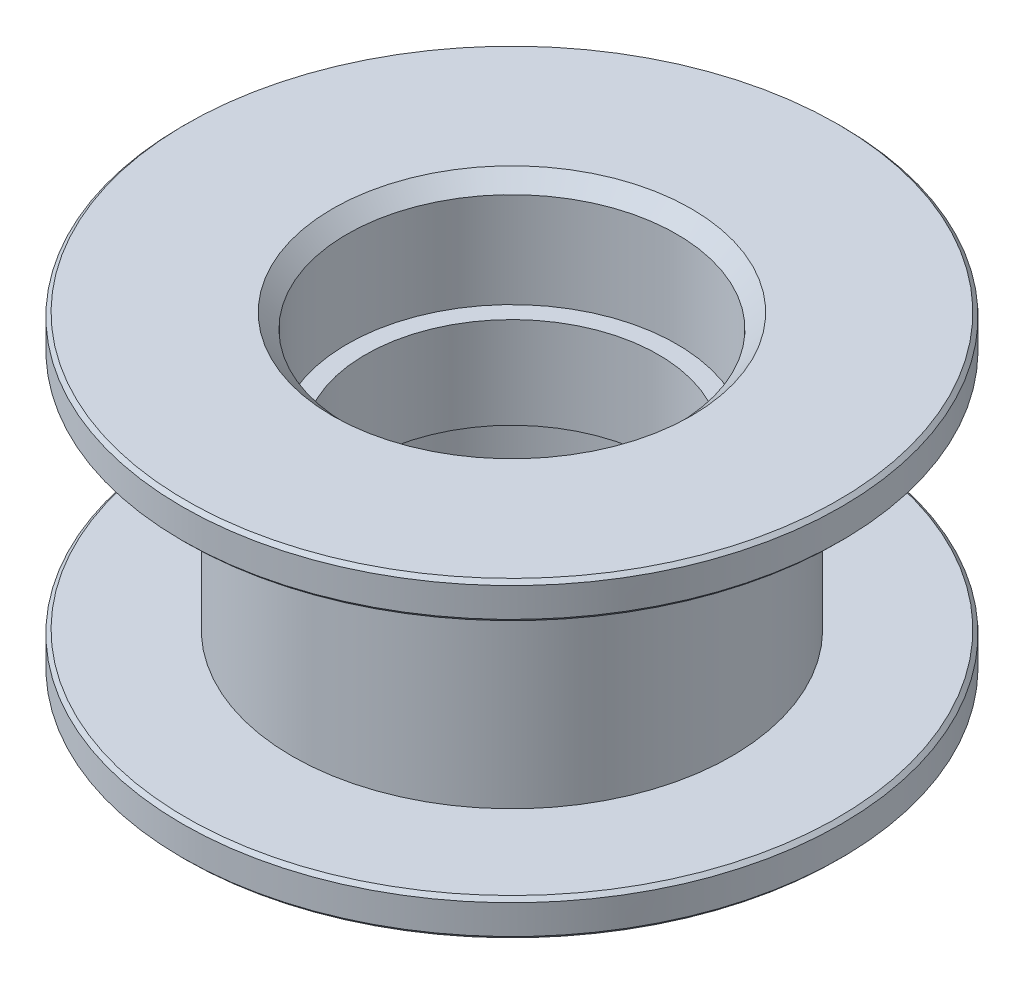
SolidWorks part; units mm, degrees
material "6061 Alloy"
ref_plane "Front Plane" through (0, 0, 0) normal (0, 0, 1) x (1, 0, 0)
ref_plane "Top Plane" through (0, 0, 0) normal (0, 1, 0) x (1, 0, 0)
ref_plane "Right Plane" through (0, 0, 0) normal (1, 0, 0) x (0, 0, -1)
sketch "BodyS" plane through (0, 0, 0) normal (0, 0, 1) x (1, 0, 0)
  line L0 (6, -3.25) -> (6, 3.25)
  line L1 (6, 3.25) -> (9, 3.25)
  line L2 (9, 3.25) -> (9, 4.25)
  line L3 (9, 4.25) -> (4.5, 4.25)
  line L4 (4.5, 4.25) -> (4.5, 1.25)
  line L5 (4.5, 1.25) -> (4, 1.25)
  line L6 (4, 1.25) -> (4, -1.25)
  line L7 (4, -1.25) -> (4.5, -1.25)
  line L8 (4.5, -1.25) -> (4.5, -4.25)
  line L9 (4.5, -4.25) -> (9, -4.25)
  line L10 (9, -4.25) -> (9, -3.25)
  line L11 (9, -3.25) -> (6, -3.25)
  line L12 (0, 0) -> (4, 0) construction
  line L13 (0, 4.25) -> (0, -4.25) construction
  dimension "BearingOD" = 9
  dimension "Height" = 8.5
  dimension "FlangeHeight" = 1
  dimension "BearingHeight" = 3
  dimension "BearingRestDiaControl" = 0.5
  dimension "RefBodyInnerDiameter" = 8
  dimension "FlangeDiaControl" = 4.5
  dimension "RefFlangeDia" = 18
  dimension "BeltPathDiaControl" = 1.5
  dimension "RefBeltPathDia" = 12
revolve "Body" add sketch "BodyS" angle 360 about L13
chamfer "InnerC" distance 0.4 angle 45 2 edges at (0, -4.25, 4.5) (0, 4.25, 4.5)
chamfer "OuterC" distance 0.1 angle 45 4 edges at (0, -4.25, 9) (0, -3.25, 9) (0, 3.25, 9) (0, 4.25, 9)
sketch "Esquisse1" plane through (0, 4.25, 0) normal (0, 1, 0) x (1, 0, 0)
  circle A0 centre (0, 0) radius 9
  circle A1 centre (0, 0) radius 9 construction
